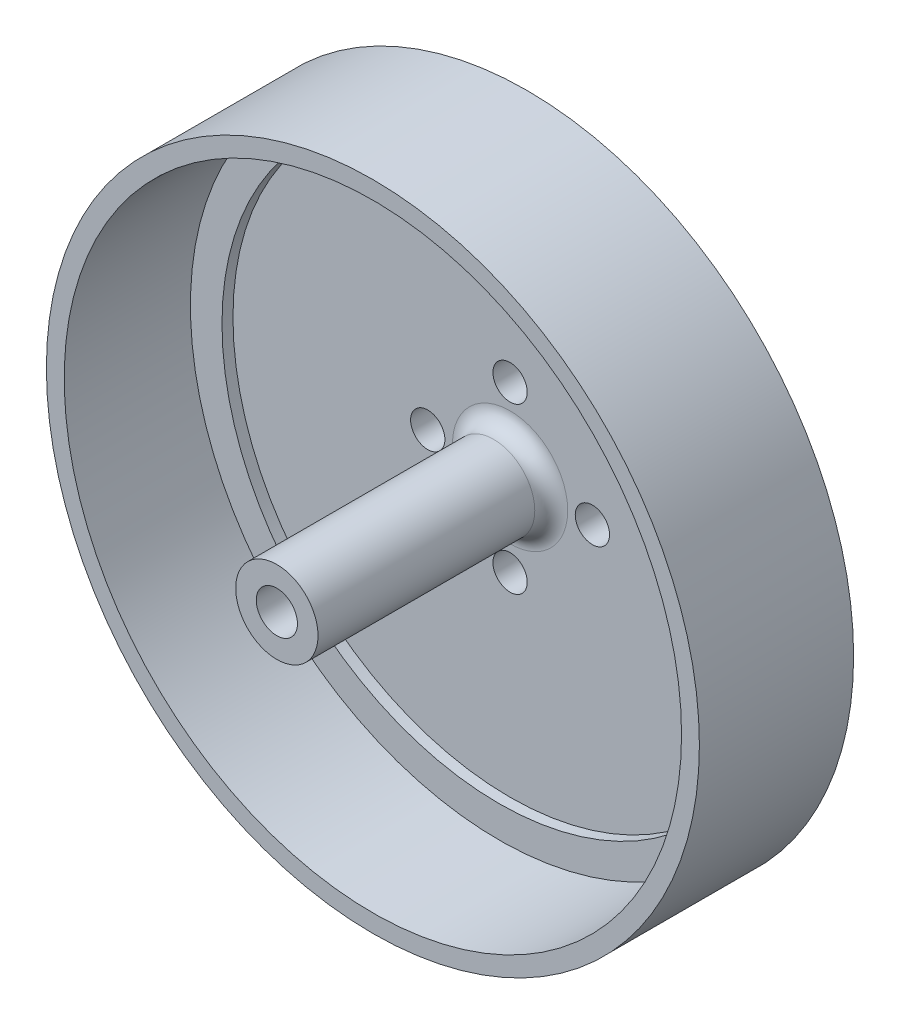
SolidWorks part; units mm, degrees
other "Marca1"
sketch "Croquis3" plane through (-23.8, -23.8, -4) normal (-0.3933, -0.8304, -0.3947) x (-0.8044, 0.5187, -0.2897)
material "Plain Carbon Steel"
ref_plane "Front Plane" through (0, 0, 0) normal (0, 0, 1) x (1, 0, 0)
ref_plane "Top Plane" through (0, 0, 0) normal (0, 1, 0) x (1, 0, 0)
ref_plane "Right Plane" through (0, 0, 0) normal (1, 0, 0) x (0, 0, -1)
sketch "Sketch1" plane through (0, 0, 0) normal (0, 0, 1) x (1, 0, 0)
  circle A0 centre (0, 0) radius 23.8
  dimension "D2" = 47.6
extrude "Boss-Extrude1" add sketch "Sketch1" along normal blind 2.3
sketch "Sketch2" plane through (0, 0, 2.3) normal (0, 0, 1) x (1, 0, 0)
  circle A0 centre (0, 0) radius 23.8
  circle A1 centre (0, 0) radius 20.2
  dimension "D1" = 40.4
extrude "Boss-Extrude2" add sketch "Sketch2" along normal blind 10
sketch "Sketch3" plane through (0, 0, 2.3) normal (0, 0, 1) x (1, 0, 0)
  circle A0 centre (0, 0) radius 3
extrude "Boss-Extrude3" add sketch "Sketch3" along normal blind 17
chamfer "Chamfer1" distance 6 angle 10 1 edges at (23.8, 0, 0)
sketch "Sketch4" plane through (0, 0, 0) normal (0, 0, -1) x (-1, 0, 0)
  circle A0 centre (0, 0) radius 6 construction
  circle A1 centre (6, 0) radius 1.25
  circle A2 centre (0, -6) radius 1.25
  circle A3 centre (-6, 0) radius 1.25
  circle A4 centre (0, 6) radius 1.25
  point P14 (0, 0)
  dimension "D1" = 12
  dimension "D2" = 4
  dimension "D3" = 2.5
extrude "Cut-Extrude1" cut sketch "Sketch4" against normal blind 15
sketch "Sketch6" plane through (0, 0, 12.3) normal (0, 0, 1) x (1, 0, 0)
  circle A0 centre (0, 0) radius 22.5
  circle A1 centre (0, 0) radius 20.2
extrude "Cut-Extrude3" cut sketch "Sketch6" against normal blind 9.2
sketch "Sketch7" plane through (0, 0, 19.3) normal (0, 0, 1) x (1, 0, 0)
  circle A0 centre (0, 0) radius 1.5
  dimension "D1" = 3
extrude "Cut-Extrude4" cut sketch "Sketch7" against normal blind 5
fillet "Redondeo1" radius 1.2 1 edges at (3, 0, 2.3)
sketch "Croquis1" plane through (0, 0, 0) normal (0, 0, -1) x (-1, 0, 0)
  circle A0 centre (0, 0) radius 9.3393
  circle A1 centre (0, 6) radius 1.25
  circle A2 centre (6, 0) radius 1.25
  circle A3 centre (0, -6) radius 1.25
  circle A4 centre (-6, 0) radius 1.25
  circle A5 centre (-6, 0) radius 1.25 construction
extrude "Saliente-Extruir1" add sketch "Croquis1" along normal blind 1.6
sketch "Croquis2" plane through (0, 0, -1.6) normal (0, 0, -1) x (-1, 0, 0)
  circle A0 centre (0, 0) radius 2
  dimension "D1" = 4
extrude "Saliente-Extruir2" add sketch "Croquis2" along normal blind 3
sketch "Croquis4" plane through (0, 0, -4.6) normal (0, 0, -1) x (-1, 0, 0)
  circle A0 centre (0, 0) radius 4.6543
extrude "Cortar-Extruir1" cut sketch "Croquis4" against normal blind 2.35
